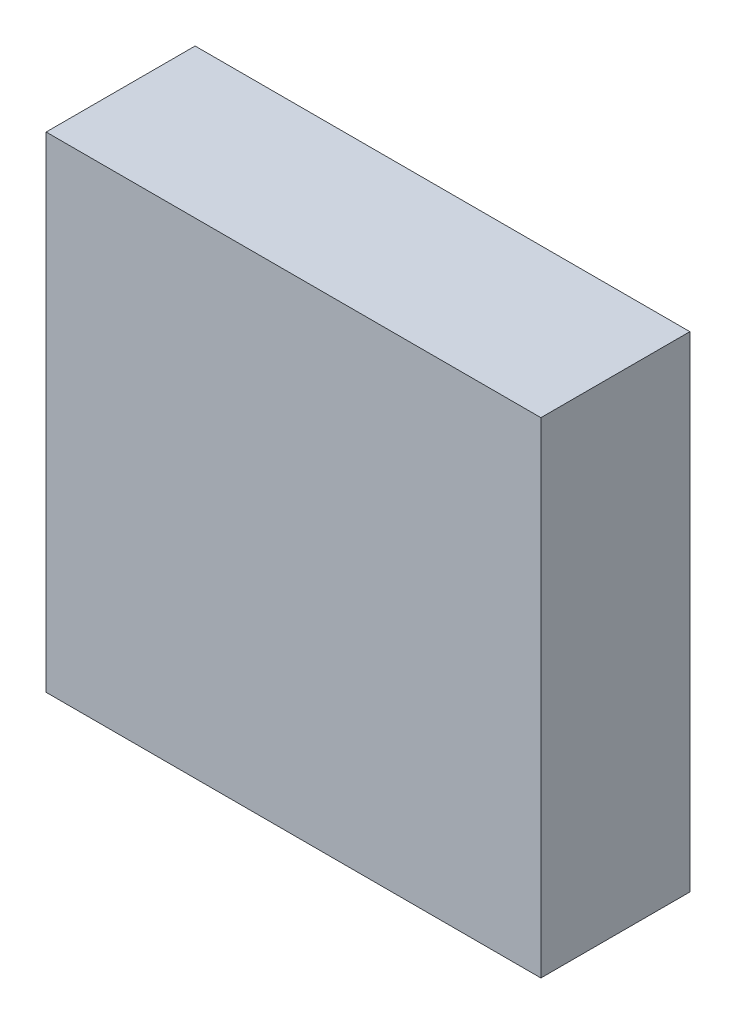
SolidWorks part; units mm, degrees
ref_plane "Front Plane" through (0, 0, 0) normal (0, 0, 1) x (1, 0, 0)
ref_plane "Top Plane" through (0, 0, 0) normal (0, 1, 0) x (1, 0, 0)
ref_plane "Right Plane" through (0, 0, 0) normal (1, 0, 0) x (0, 0, -1)
sketch "Sketch1" plane through (0, 0, 0) normal (0, 0, 1) x (1, 0, 0)
  line L0 (-1.7577, 1.7575) -> (1.5635, 1.7575)
  line L1 (1.5635, 1.7575) -> (1.5635, -1.5)
  line L2 (1.5635, -1.5) -> (-1.7577, -1.5)
  line L3 (-1.7577, -1.5) -> (-1.7577, 1.7575)
extrude "Component_Outline" add sketch "Sketch1" along normal blind 1 separate body
sketch3d "3DSketch1"
  line L0 (0, 0, 0) -> (1, 0, 0)
  line L1 (0, 0, 0) -> (0, 1, 0)
  line L2 (0, 0, 0) -> (0, 0, 1)
  point P0 (0, 0, 0)
